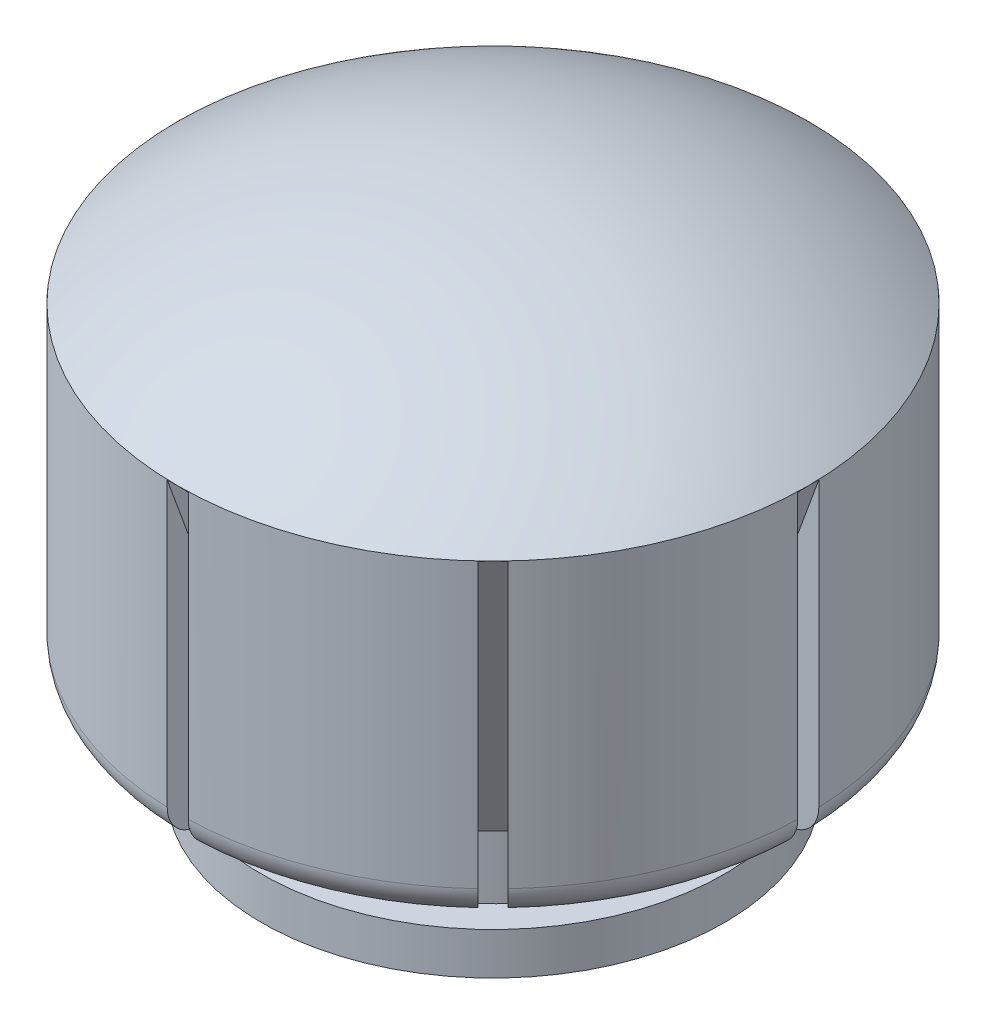
SolidWorks part; units mm, degrees
ref_plane "Front Plane" through (0, 0, 0) normal (0, 0, 1) x (1, 0, 0)
ref_plane "Top Plane" through (0, 0, 0) normal (0, 1, 0) x (1, 0, 0)
ref_plane "Right Plane" through (0, 0, 0) normal (1, 0, 0) x (0, 0, -1)
sketch "Sketch3" plane through (0, 0, 0) normal (0, 0, 1) x (1, 0, 0)
  line L0 (0, 0) -> (50000, 0) construction
  line L1 (0, 0) -> (0, 50000) construction
  line L2 (0, 0) -> (22, 0)
  line L3 (22, 0) -> (22, 4)
  line L4 (22, 4) -> (19, 4)
  line L5 (19, 4) -> (19, 10)
  line L6 (19, 10) -> (30, 10)
  line L7 (30, 10) -> (30, 40)
  line L8 (0, 50) -> (0, 0)
  arc A0 (30, 40) -> (0, 50) centre (0, 0) ccw
  dimension "D1" = 100
  dimension "D2" = 44
  dimension "D3" = 38
  dimension "D4" = 60
  dimension "D5" = 4
  dimension "D6" = 10
revolve "Revolve1" add sketch "Sketch3" angle 360 about L1
sketch "Sketch6" plane through (0, 0, 0) normal (0, -1, 0) x (1, 0, 0)
  point P0 (0, 0)
hole_wizard "M16 Tapped Hole1" positions "Sketch6" profile "Sketch5" tap size "M16" standard "ISO"
sketch "Sketch5" plane through (0, 0, 0) normal (1, 0, 0) x (0, 0, -1)
  line L0 (0, 0) -> (0, 39.206)
  line L1 (0, 39.206) -> (7, 35)
  line L2 (7, 35) -> (7, 0)
  line L5 (7, 0) -> (0, 0)
  line L10 (0, 39.206) -> (-7, 35) construction
  line L11 (0, -6.35) -> (0, 107.95) construction
  dimension "Tap Drill Dia." = 14
  dimension "Tap Drill Depth" = 35
  dimension "Drill Angle" = 118
cosmetic thread "Hole Thread1" parameters "D1"=32, "D2"=16
sketch "Sketch7" plane through (0, 0, 0) normal (0, 0, 1) x (1, 0, 0)
  line L0 (30, 40) -> (30, 10)
  line L1 (30, 10) -> (30, 40) construction
  line L2 (30, 10) -> (19, 10)
  line L3 (19, 10) -> (30, 40)
  point P5 (0, 0)
  point P7 (0, 0)
extrude "Cut-Extrude1" cut sketch "Sketch7" against normal mid plane 2
pattern_circular "CirPattern1" count 8 over 360 about axis through (0, 0, 0) along (0, 1, 0) of "Cut-Extrude1"
fillet "Fillet1" radius 3 8 edges at (-11.4805, 10, 27.7164) (-27.7164, 10, 11.4805) (-27.7164, 10, -11.4805) (-11.4805, 10, -27.7164) (11.4805, 10, -27.7164) (27.7164, 10, -11.4805) (27.7164, 10, 11.4805) (11.4805, 10, 27.7164)
